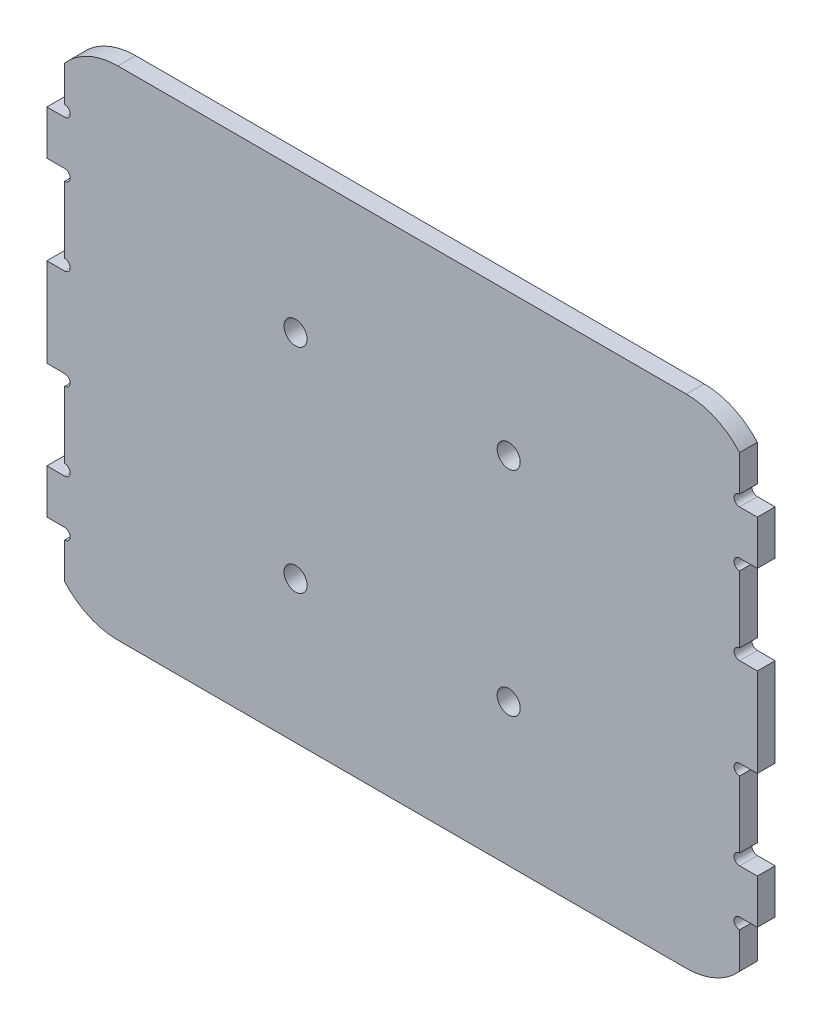
SolidWorks part; units mm, degrees
ref_plane "前视基准面" through (0, 0, 0) normal (0, 0, 1) x (1, 0, 0)
ref_plane "上视基准面" through (0, 0, 0) normal (0, 1, 0) x (1, 0, 0)
ref_plane "右视基准面" through (0, 0, 0) normal (1, 0, 0) x (0, 0, -1)
other "Configuration Table"
sketch "草图1" plane through (0, 0, 0) normal (0, 0, 1) x (1, 0, 0)
  line L0 (0, 0) -> (284.1069, 0) construction
  line L1 (-100, 120) -> (100, 120)
  line L2 (-100, 120) -> (-100, -20)
  line L3 (-100, -20) -> (100, -20)
  line L4 (100, 120) -> (100, -20)
  line L5 (0, 0) -> (0, 194.938) construction
  circle A0 centre (30, 80) radius 3.25
  circle A1 centre (30, 20) radius 3.25
  circle A2 centre (-30, 80) radius 3.25
  circle A3 centre (-30, 20) radius 3.25
  dimension "D3" = 6.5
  dimension "D6" = 40
  dimension "D1" = 120
  dimension "D2" = 200
  dimension "D4" = 30
  dimension "D5" = 60
  dimension "D7" = 20
extrude "凸台-拉伸1" add sketch "草图1" along normal blind 5
fillet "圆角1" radius 20 4 edges at (-100, 120, 2.5) (-100, -20, 2.5) (100, -20, 2.5) (100, 120, 2.5)
sketch "草图3" plane through (0, 0, 5) normal (0, 0, 1) x (1, 0, 0)
  line L0 (0, 126.8429) -> (0, -134.2378) construction
  line L1 (-131.0539, 0) -> (117.702, 0) construction
  line L2 (100, 100) -> (100, 0) construction
  line L3 (95, 87.5) -> (100, 87.5)
  line L4 (95, 87.5) -> (95, 62.5)
  line L5 (95, 62.5) -> (100, 62.5)
  line L6 (100, 87.5) -> (100, 62.5)
  line L8 (95, 37.5) -> (100, 37.5)
  line L9 (95, 37.5) -> (95, 12.5)
  line L10 (95, 12.5) -> (100, 12.5)
  line L11 (100, 37.5) -> (100, 12.5)
  line L26 (-100, 37.5) -> (-100, 12.5)
  line L27 (-95, 12.5) -> (-100, 12.5)
  line L28 (-95, 37.5) -> (-95, 12.5)
  line L29 (-95, 37.5) -> (-100, 37.5)
  line L31 (-100, 87.5) -> (-100, 62.5)
  line L32 (-95, 62.5) -> (-100, 62.5)
  line L33 (-95, 87.5) -> (-95, 62.5)
  line L34 (-95, 87.5) -> (-100, 87.5)
  line L35 (-115.6764, 50) -> (189.5806, 50) construction
  line L36 (-80, -20) -> (80, -20) construction
  line L37 (-80, 120) -> (80, 120) construction
  line L38 (-95, -22.8075) -> (-100, -22.8075)
  line L39 (95, 0) -> (100, 0)
  line L40 (95, 0) -> (95, -22.8075)
  line L41 (95, -22.8075) -> (100, -22.8075)
  line L42 (100, 0) -> (100, -22.8075)
  line L43 (-100, 0) -> (-100, -22.8075)
  line L44 (-95, 0) -> (-100, 0)
  line L45 (-95, 0) -> (-95, -22.8075)
  line L46 (-95, 100) -> (-95, 122.8075)
  line L47 (-95, 100) -> (-100, 100)
  line L48 (-100, 100) -> (-100, 122.8075)
  line L49 (-95, 122.8075) -> (-100, 122.8075)
  line L50 (95, 122.8075) -> (100, 122.8075)
  line L51 (100, 100) -> (100, 122.8075)
  line L52 (95, 100) -> (100, 100)
  line L53 (95, 100) -> (95, 122.8075)
  arc A0 (80, -20) -> (100, 0) centre (80, 0) ccw construction
  point P25 (78.9203, 0)
  point P26 (100, 0)
  dimension "D1" = 5
  dimension "D2" = 5
  dimension "D3" = 5
  dimension "D4" = 25
  dimension "D5" = 25
  dimension "D6" = 25
extrude "切除-拉伸1" cut sketch "草图3" against normal blind 39
sketch "草图4" plane through (0, 0, 5) normal (0, 0, 1) x (1, 0, 0)
  line L0 (95, 87.5) -> (95, 62.5) construction
  line L1 (95, 37.5) -> (95, 12.5) construction
  line L2 (0, 0) -> (0, 130.3564) construction
  line L3 (100, 87.5) -> (95, 87.5) construction
  line L4 (95, 62.5) -> (100, 62.5) construction
  line L5 (100, 37.5) -> (95, 37.5) construction
  line L6 (95, 12.5) -> (100, 12.5) construction
  line L7 (95, 0) -> (95, -13.2288) construction
  line L8 (100, 0) -> (95, 0) construction
  line L9 (-95, 0) -> (-100, 0) construction
  line L10 (-95, -13.2288) -> (-95, 0) construction
  line L11 (95, 113.2288) -> (95, 100) construction
  line L12 (-95, 100) -> (-95, 113.2288) construction
  line L13 (95, 100) -> (100, 100) construction
  line L14 (-100, 100) -> (-95, 100) construction
  circle A0 centre (95, 85.95) radius 1.55
  circle A1 centre (95, 64.05) radius 1.55
  circle A2 centre (95, 35.95) radius 1.55
  circle A3 centre (95, 14.05) radius 1.55
  circle A4 centre (-95, 14.05) radius 1.55
  circle A5 centre (-95, 35.95) radius 1.55
  circle A6 centre (-95, 64.05) radius 1.55
  circle A7 centre (-95, 85.95) radius 1.55
  circle A8 centre (95, -1.55) radius 1.55
  circle A9 centre (-95, -1.55) radius 1.55
  circle A10 centre (95, 101.55) radius 1.55
  circle A11 centre (-95, 101.55) radius 1.55
  dimension "D1" = 3.1
extrude "切除-拉伸2" cut sketch "草图4" against normal blind 10
